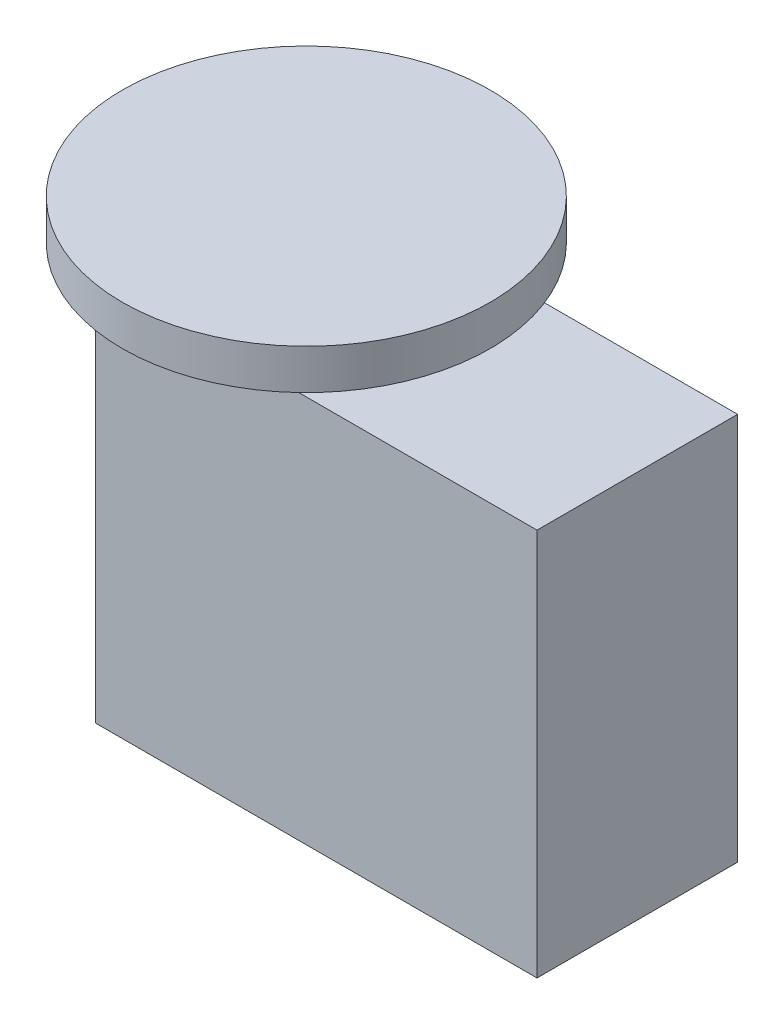
SolidWorks part; units mm, degrees
ref_plane "Front Plane" through (0, 0, 0) normal (0, 0, 1) x (1, 0, 0)
ref_plane "Top Plane" through (0, 0, 0) normal (0, 1, 0) x (1, 0, 0)
ref_plane "Right Plane" through (0, 0, 0) normal (1, 0, 0) x (0, 0, -1)
sketch "Sketch2" plane through (0, 0, 0) normal (0, 1, 0) x (1, 0, 0)
  line L1 (-79.5681, -19.8609) -> (-13.5681, -19.8609)
  line L2 (-79.5681, -19.8609) -> (-79.5681, -49.8609)
  line L3 (-79.5681, -49.8609) -> (-13.5681, -49.8609)
  line L4 (-13.5681, -19.8609) -> (-13.5681, -49.8609)
  dimension "D1" = 66
  dimension "D2" = 30
extrude "Boss-Extrude1" add sketch "Sketch2" along normal blind 58
sketch "Sketch3" plane through (0, 58, 0) normal (0, 1, 0) x (1, 0, 0)
  line L0 (-79.5681, -19.8609) -> (-13.5681, -49.8609) construction
  line L1 (-79.5681, -49.8609) -> (-13.5681, -19.8609) construction
  line L2 (-46.5681, -34.8609) -> (-46.5681, -49.8609) construction
  line L3 (-79.5681, -49.8609) -> (-13.5681, -49.8609) construction
  line L4 (-46.5681, -49.8609) -> (-79.5681, -49.8609) construction
  line L5 (-63.0681, -49.8609) -> (-63.0681, -19.8609) construction
  line L6 (-13.5681, -19.8609) -> (-79.5681, -19.8609) construction
  circle A0 centre (-63.0681, -34.8609) radius 7.5
  circle A1 centre (-63.0681, -34.8609) radius 9
  dimension "D1" = 15
  dimension "D2" = 18
extrude "Boss-Extrude2" add sketch "Sketch3" along normal blind 2
sketch "Sketch4" plane through (0, 58, 0) normal (0, 1, 0) x (1, 0, 0)
  circle A0 centre (-63.0681, -34.8609) radius 2.5
  dimension "D1" = 5
extrude "Boss-Extrude3" add sketch "Sketch4" along normal blind 10
sketch "Sketch5" plane through (0, 68, 0) normal (0, 1, 0) x (1, 0, 0)
  circle A0 centre (-63.0681, -34.8609) radius 27.5
  dimension "D1" = 55
extrude "Boss-Extrude4" add sketch "Sketch5" along normal blind 1 and the other way blind 5
sketch "Sketch6" plane through (0, 0, 0) normal (0, -1, 0) x (1, 0, 0)
  line L0 (-79.5681, 19.8609) -> (-79.5681, 49.8609) construction
  line L1 (-69.5681, 24.8609) -> (-63.5681, 24.8609)
  line L2 (-69.5681, 24.8609) -> (-69.5681, 44.8609)
  line L3 (-69.5681, 44.8609) -> (-63.5681, 44.8609)
  line L4 (-63.5681, 24.8609) -> (-63.5681, 44.8609)
  line L5 (-13.5681, 49.8609) -> (-13.5681, 19.8609) construction
  line L6 (-79.5681, 49.8609) -> (-13.5681, 49.8609) construction
  line L7 (-13.5681, 19.8609) -> (-79.5681, 19.8609) construction
  dimension "D1" = 10
  dimension "D2" = 50
  dimension "D3" = 5
  dimension "D4" = 5
extrude "Boss-Extrude5" add sketch "Sketch6" along normal blind 3
sketch "Sketch7" plane through (0, -3, 0) normal (0, -1, 0) x (1, 0, 0)
  line L0 (-69.5681, 24.8609) -> (-63.5681, 44.8609) construction
  line L1 (-69.5681, 24.8609) -> (-63.5681, 24.8609) construction
  line L2 (-69.5681, 44.8609) -> (-69.5681, 24.8609) construction
  line L3 (-63.5681, 24.8609) -> (-63.5681, 44.8609) construction
  line L4 (-63.5681, 44.8609) -> (-69.5681, 44.8609) construction
  line L5 (-63.5681, 44.8609) -> (-63.5681, 34.8609) construction
  line L6 (-63.5681, 24.8609) -> (-63.5681, 34.8609) construction
  line L7 (-63.5681, 34.8609) -> (-63.5681, 44.8609) construction
  line L8 (-63.5681, 24.8609) -> (-69.5681, 44.8609) construction
  line L9 (-63.5681, 34.8609) -> (-63.5681, 24.8609) construction
  line L10 (-63.5681, 24.8609) -> (-63.5681, 34.8609) construction
  line L11 (-63.5681, 34.8609) -> (-63.5681, 44.8609) construction
  line L12 (-63.5681, 29.8609) -> (-69.5681, 29.8609) construction
  line L13 (-63.5681, 39.8609) -> (-69.5681, 39.8609) construction
  circle A0 centre (-66.5681, 29.8609) radius 1
  circle A1 centre (-66.5681, 39.8609) radius 1
  dimension "D1" = 2
  dimension "D2" = 2
extrude "Boss-Extrude6" add sketch "Sketch7" along normal blind 3
ref_plane "Plane1" through (-79.5681, 0, 19.8609) normal (0, 0, 1) x (1, 0, 0)
